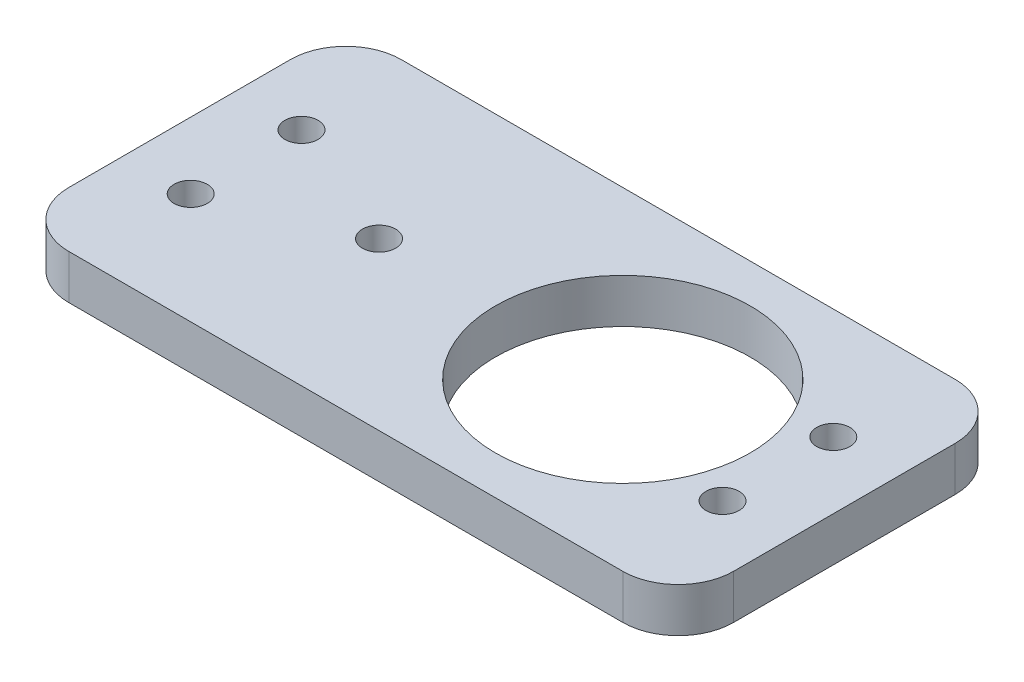
SolidWorks part; units mm, degrees
ref_plane "前视基准面" through (0, 0, 0) normal (0, 0, 1) x (1, 0, 0)
ref_plane "上视基准面" through (0, 0, 0) normal (0, 1, 0) x (1, 0, 0)
ref_plane "右视基准面" through (0, 0, 0) normal (1, 0, 0) x (0, 0, -1)
sketch "草图1" plane through (0, 0, 0) normal (0, 1, 0) x (1, 0, 0)
  line L1 (-30, -15) -> (30, -15)
  line L2 (-30, -15) -> (-30, 15)
  line L3 (-30, 15) -> (30, 15)
  line L4 (30, -15) -> (30, 15)
  line L5 (-30, -15) -> (30, 15) construction
  line L6 (-30, 15) -> (30, -15) construction
  point P0 (0, 0)
  dimension "D1" = 30
  dimension "D2" = 60
extrude "凸台-拉伸1" add sketch "草图1" along normal blind 4
sketch "草图2" plane through (0, 4, 0) normal (0, 1, 0) x (1, 0, 0)
  line L1 (-24, -5) -> (24, -5) construction
  line L2 (-24, -5) -> (-24, 5) construction
  line L3 (-24, 5) -> (24, 5) construction
  line L4 (24, -5) -> (24, 5) construction
  line L5 (-24, -5) -> (24, 5) construction
  line L6 (-24, 5) -> (24, -5) construction
  circle A0 centre (-24, 5) radius 1.5
  circle A1 centre (-24, -5) radius 1.5
  circle A2 centre (24, -5) radius 1.5
  circle A3 centre (24, 5) radius 1.5
  point P0 (0, 0)
  dimension "D3" = 3
  dimension "D1" = 48
  dimension "D2" = 10
extrude "切除-拉伸1" cut sketch "草图2" against normal blind 4
sketch "草图3" plane through (0, 4, 0) normal (0, 1, 0) x (1, 0, 0)
  circle A0 centre (10, 0) radius 11.5
  circle A1 centre (24, -5) radius 1.5 construction
  point P4 (0, 0)
  dimension "D2" = 23
  dimension "D1" = 14
extrude "切除-拉伸2" cut sketch "草图3" against normal blind 4
sketch "草图4" plane through (0, 4, 0) normal (0, 1, 0) x (1, 0, 0)
  circle A0 centre (-12, 0) radius 1.5
  circle A1 centre (10, 0) radius 11.5 construction
  point P2 (-11, 0)
  dimension "D1" = 3
  dimension "D2" = 22
extrude "切除-拉伸3" cut sketch "草图4" against normal blind 4
fillet "圆角1" radius 5 4 edges at (-30, 2, 15) (-30, 2, -15) (30, 2, -15) (30, 2, 15)
